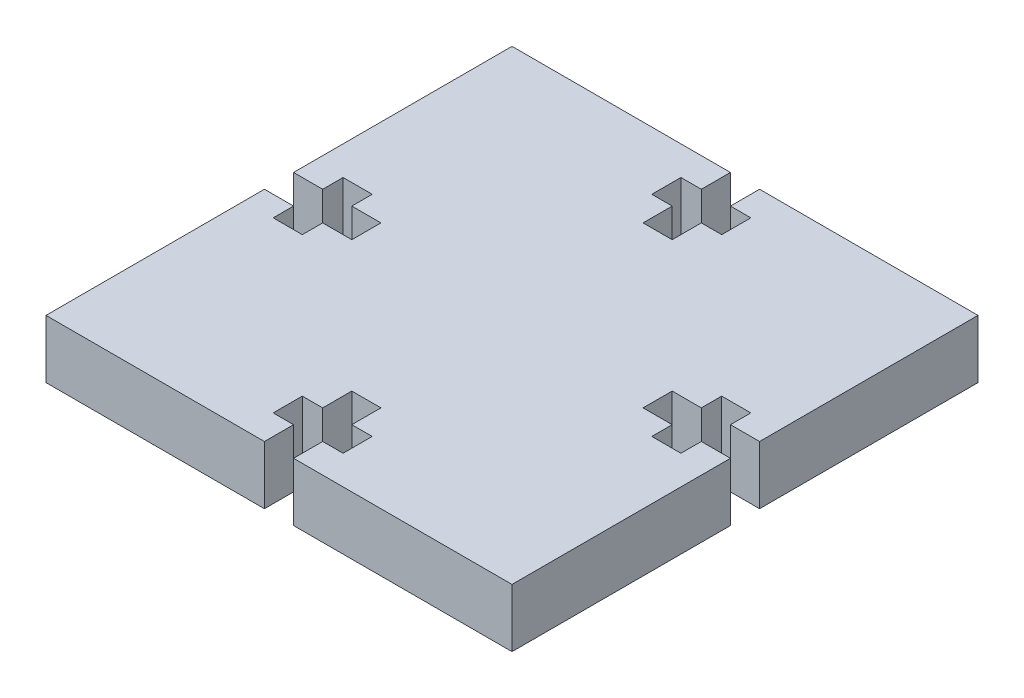
SolidWorks part; units mm, degrees
ref_plane "Front Plane" through (0, 0, 0) normal (0, 0, 1) x (1, 0, 0)
ref_plane "Top Plane" through (0, 0, 0) normal (0, 1, 0) x (1, 0, 0)
ref_plane "Right Plane" through (0, 0, 0) normal (1, 0, 0) x (0, 0, -1)
sketch "Sketch1" plane through (0, 0, 0) normal (0, 1, 0) x (1, 0, 0)
  line L1 (0, 0) -> (50.8, 0)
  line L2 (0, 0) -> (0, 50.8)
  line L3 (0, 50.8) -> (50.8, 50.8)
  line L4 (50.8, 0) -> (50.8, 50.8)
  dimension "D1" = 50.8
  dimension "D2" = 50.8
extrude "Boss-Extrude1" add sketch "Sketch1" along normal blind 6.35
sketch "Sketch2" plane through (0, 6.35, 0) normal (0, 1, 0) x (1, 0, 0)
  line L0 (25.4, 50.8) -> (25.4, 46.0375) construction
  line L1 (21.59, 47.625) -> (23.8125, 47.625)
  line L2 (21.59, 47.625) -> (21.59, 44.45)
  line L3 (21.59, 44.45) -> (23.8125, 44.45)
  line L4 (29.21, 47.625) -> (29.21, 44.45)
  line L5 (21.59, 47.625) -> (29.21, 44.45) construction
  line L6 (21.59, 44.45) -> (29.21, 47.625) construction
  line L7 (23.8125, 41.275) -> (26.9875, 41.275)
  line L8 (23.8125, 41.275) -> (23.8125, 44.45)
  line L9 (23.8125, 50.8) -> (26.9875, 50.8)
  line L10 (26.9875, 41.275) -> (26.9875, 44.45)
  line L11 (23.8125, 41.275) -> (26.9875, 50.8) construction
  line L12 (23.8125, 50.8) -> (26.9875, 41.275) construction
  line L13 (50.8, 50.8) -> (0, 50.8) construction
  line L14 (-55, 0) -> (55, 0) construction
  line L15 (50.8, 25.4) -> (0, 25.4) construction
  line L16 (50.8, 0) -> (50.8, 50.8) construction
  line L17 (0, -55) -> (0, 55) construction
  line L18 (23.8125, 47.625) -> (23.8125, 50.8)
  line L19 (26.9875, 47.625) -> (29.21, 47.625)
  line L20 (25.4, 46.0375) -> (25.4, 0) construction
  line L21 (26.9875, 47.625) -> (26.9875, 50.8)
  line L22 (26.9875, 44.45) -> (29.21, 44.45)
  line L23 (23.8125, 0) -> (26.9875, 9.525) construction
  line L24 (23.8125, 9.525) -> (26.9875, 0) construction
  line L25 (21.59, 6.35) -> (29.21, 3.175) construction
  line L26 (21.59, 3.175) -> (29.21, 6.35) construction
  line L27 (25.4, 0) -> (25.4, 4.7625) construction
  line L28 (26.9875, 6.35) -> (29.21, 6.35)
  line L29 (26.9875, 3.175) -> (26.9875, 0)
  line L30 (26.9875, 3.175) -> (29.21, 3.175)
  line L31 (23.8125, 3.175) -> (23.8125, 0)
  line L32 (26.9875, 9.525) -> (26.9875, 6.35)
  line L33 (23.8125, 0) -> (26.9875, 0)
  line L34 (23.8125, 9.525) -> (23.8125, 6.35)
  line L35 (23.8125, 9.525) -> (26.9875, 9.525)
  line L36 (29.21, 3.175) -> (29.21, 6.35)
  line L37 (21.59, 6.35) -> (23.8125, 6.35)
  line L38 (21.59, 3.175) -> (21.59, 6.35)
  line L39 (21.59, 3.175) -> (23.8125, 3.175)
  line L40 (3.175, 26.9875) -> (3.175, 29.21)
  line L41 (9.525, 23.8125) -> (6.35, 23.8125)
  line L42 (9.525, 23.8125) -> (9.525, 26.9875)
  line L43 (9.525, 26.9875) -> (6.35, 26.9875)
  line L44 (0, 23.8125) -> (0, 26.9875)
  line L45 (9.525, 23.8125) -> (0, 26.9875) construction
  line L46 (9.525, 26.9875) -> (0, 23.8125) construction
  line L47 (3.175, 21.59) -> (6.35, 21.59)
  line L48 (3.175, 21.59) -> (3.175, 23.8125)
  line L49 (3.175, 29.21) -> (6.35, 29.21)
  line L50 (6.35, 21.59) -> (6.35, 23.8125)
  line L51 (3.175, 21.59) -> (6.35, 29.21) construction
  line L52 (3.175, 29.21) -> (6.35, 21.59) construction
  line L53 (3.175, 26.9875) -> (0, 26.9875)
  line L54 (6.35, 26.9875) -> (6.35, 29.21)
  line L55 (3.175, 23.8125) -> (0, 23.8125)
  line L56 (47.625, 29.21) -> (44.45, 21.59) construction
  line L57 (47.625, 21.59) -> (44.45, 29.21) construction
  line L58 (41.275, 26.9875) -> (50.8, 23.8125) construction
  line L59 (41.275, 23.8125) -> (50.8, 26.9875) construction
  line L60 (47.625, 23.8125) -> (50.8, 23.8125)
  line L61 (44.45, 26.9875) -> (44.45, 29.21)
  line L62 (47.625, 26.9875) -> (50.8, 26.9875)
  line L63 (44.45, 21.59) -> (44.45, 23.8125)
  line L64 (47.625, 29.21) -> (44.45, 29.21)
  line L65 (47.625, 21.59) -> (47.625, 23.8125)
  line L66 (47.625, 21.59) -> (44.45, 21.59)
  line L67 (50.8, 23.8125) -> (50.8, 26.9875)
  line L68 (41.275, 26.9875) -> (44.45, 26.9875)
  line L69 (41.275, 23.8125) -> (41.275, 26.9875)
  line L70 (41.275, 23.8125) -> (44.45, 23.8125)
  line L71 (47.625, 26.9875) -> (47.625, 29.21)
  point P0 (25.4, 46.0375)
  point P5 (25.4, 46.0375)
  point P22 (25.4, 25.4)
  point P42 (4.7625, 25.4)
  point P47 (4.7625, 25.4)
  point P68 (46.0375, 25.4)
  dimension "D1" = 3.175
  dimension "D2" = 9.525
  dimension "D3" = 3.175
  dimension "D4" = 7.62
  dimension "D5" = 3.175
  dimension "D6" = 7.62
  dimension "D7" = 9.525
  dimension "D8" = 3.175
extrude "Cut-Extrude6" cut sketch "Sketch2" against normal through all
